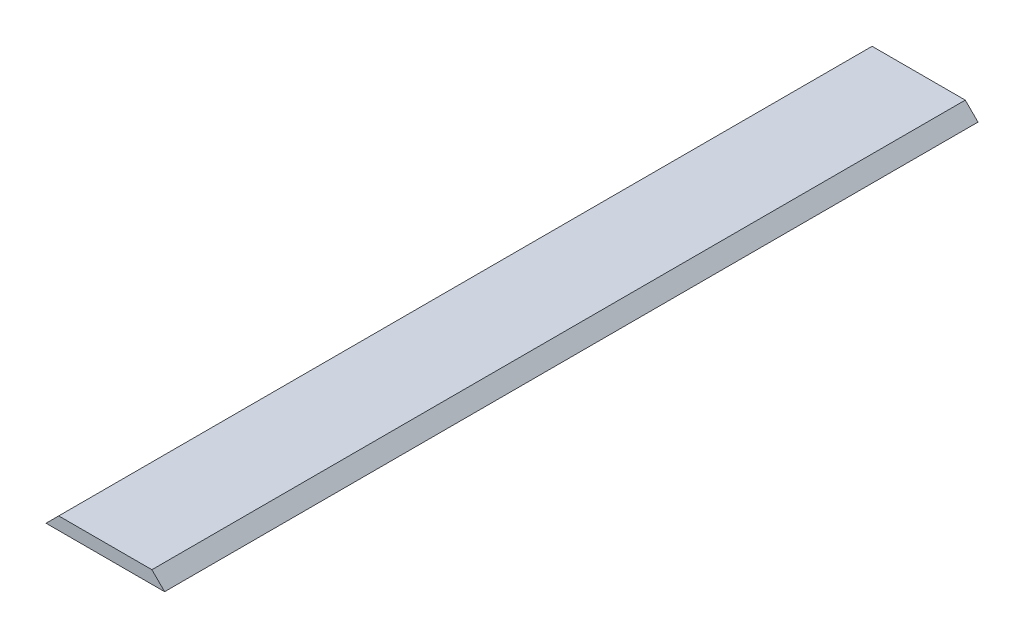
SolidWorks part; units mm, degrees
material "Pine"
ref_plane "Front Plane" through (0, 0, 0) normal (0, 0, 1) x (1, 0, 0)
ref_plane "Top Plane" through (0, 0, 0) normal (0, 1, 0) x (1, 0, 0)
ref_plane "Right Plane" through (0, 0, 0) normal (1, 0, 0) x (0, 0, -1)
sketch "Sketch1" plane through (0, 0, 0) normal (0, 0, 1) x (1, 0, 0)
  line L1 (-88.9, -9.525) -> (88.9, -9.525)
  line L2 (-88.9, -9.525) -> (-88.9, 9.525)
  line L3 (-88.9, 9.525) -> (88.9, 9.525)
  line L4 (88.9, -9.525) -> (88.9, 9.525)
  line L5 (-88.9, -9.525) -> (88.9, 9.525) construction
  line L6 (-88.9, 9.525) -> (88.9, -9.525) construction
  point P0 (0, 0)
  dimension "D1" = 19.05
  dimension "D2" = 177.8
extrude "Boss-Extrude1" add sketch "Sketch1" along normal mid plane 1219.2
sketch "Sketch2" plane through (0, 0, 609.6) normal (0, 0, 1) x (1, 0, 0)
  line L5 (-88.9, -9.525) -> (-69.85, 9.525)
  line L6 (88.9, 9.525) -> (-88.9, 9.525) construction
  line L9 (-88.9, -9.525) -> (-88.9, 9.525)
  line L11 (-88.9, 9.525) -> (-69.85, 9.525)
  line L12 (0, 9.525) -> (0, -9.525)
  line L13 (-88.9, -9.525) -> (88.9, -9.525) construction
  line L14 (88.9, 9.525) -> (69.85, 9.525)
  line L15 (88.9, -9.525) -> (88.9, 9.525)
  line L16 (88.9, -9.525) -> (69.85, 9.525)
extrude "Cut-Extrude1" cut sketch "Sketch2" against normal blind 1219.2
